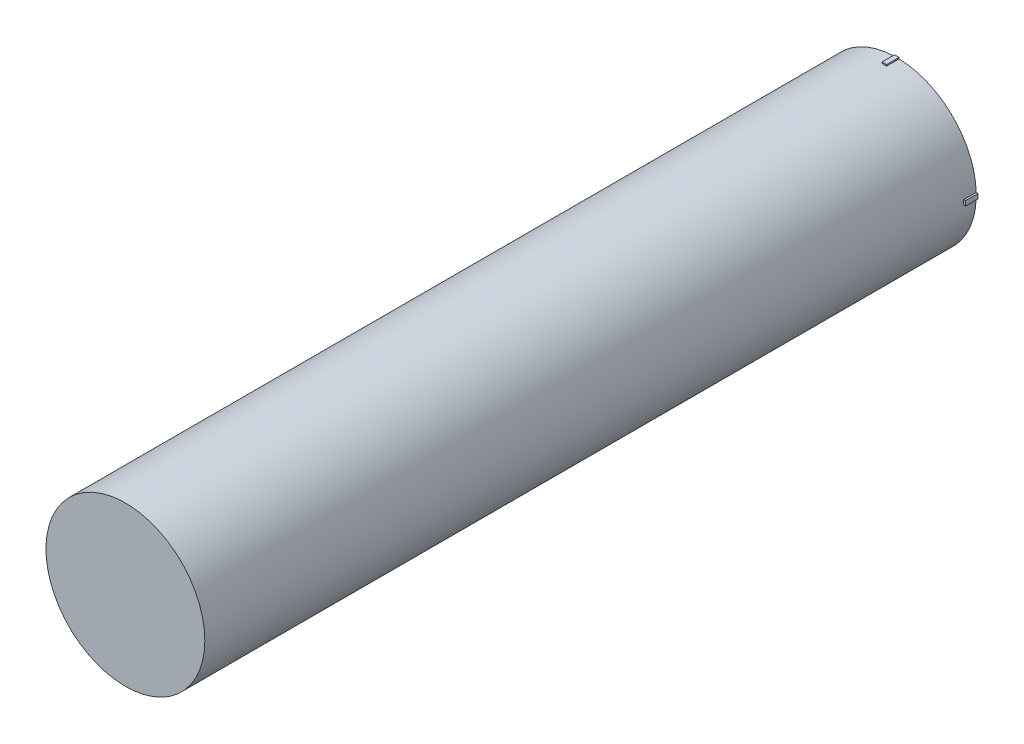
SolidWorks part; units mm, degrees
ref_plane "Alzado" through (0, 0, 0) normal (0, 0, 1) x (1, 0, 0)
ref_plane "Planta" through (0, 0, 0) normal (0, 1, 0) x (1, 0, 0)
ref_plane "Vista lateral" through (0, 0, 0) normal (1, 0, 0) x (0, 0, -1)
sketch "Croquis1" plane through (0, 0, 0) normal (0, 0, 1) x (1, 0, 0)
  circle A0 centre (0, 0) radius 19.05
  dimension "D1" = 38.1
extrude "Saliente-Extruir1" add sketch "Croquis1" along normal blind 185
sketch "Croquis2" plane through (0, 0, 0) normal (0, 0, -1) x (-1, 0, 0)
  line L1 (-19.4693, -0.5629) -> (-18.6307, -0.5629)
  line L2 (-19.4693, -0.5629) -> (-19.4693, 0.5629)
  line L3 (-19.4693, 0.5629) -> (-18.6307, 0.5629)
  line L4 (-18.6307, -0.5629) -> (-18.6307, 0.5629)
  line L5 (-19.4693, -0.5629) -> (-18.6307, 0.5629) construction
  line L6 (-19.4693, 0.5629) -> (-18.6307, -0.5629) construction
  line L7 (19.4352, -0.5629) -> (18.6648, -0.5629)
  line L8 (19.4352, -0.5629) -> (19.4352, 0.5629)
  line L9 (19.4352, 0.5629) -> (18.6648, 0.5629)
  line L10 (18.6648, -0.5629) -> (18.6648, 0.5629)
  line L11 (19.4352, -0.5629) -> (18.6648, 0.5629) construction
  line L12 (19.4352, 0.5629) -> (18.6648, -0.5629) construction
  line L13 (-0.5458, 18.7359) -> (0.5458, 18.7359)
  line L14 (-0.5458, 18.7359) -> (-0.5458, 19.3641)
  line L15 (-0.5458, 19.3641) -> (0.5458, 19.3641)
  line L16 (0.5458, 18.7359) -> (0.5458, 19.3641)
  line L17 (-0.5458, 18.7359) -> (0.5458, 19.3641) construction
  line L18 (-0.5458, 19.3641) -> (0.5458, 18.7359) construction
  line L19 (-0.5458, -19.384) -> (0.5458, -19.384)
  line L20 (-0.5458, -19.384) -> (-0.5458, -18.716)
  line L21 (-0.5458, -18.716) -> (0.5458, -18.716)
  line L22 (0.5458, -19.384) -> (0.5458, -18.716)
  line L23 (-0.5458, -19.384) -> (0.5458, -18.716) construction
  line L24 (-0.5458, -18.716) -> (0.5458, -19.384) construction
  circle A0 centre (0, 0) radius 19.05 construction
  point P0 (-19.05, 0)
  point P7 (19.05, 0)
  point P12 (0, 19.05)
  point P17 (0, -19.05)
extrude "Saliente-Extruir2" add sketch "Croquis2" against normal blind 3
